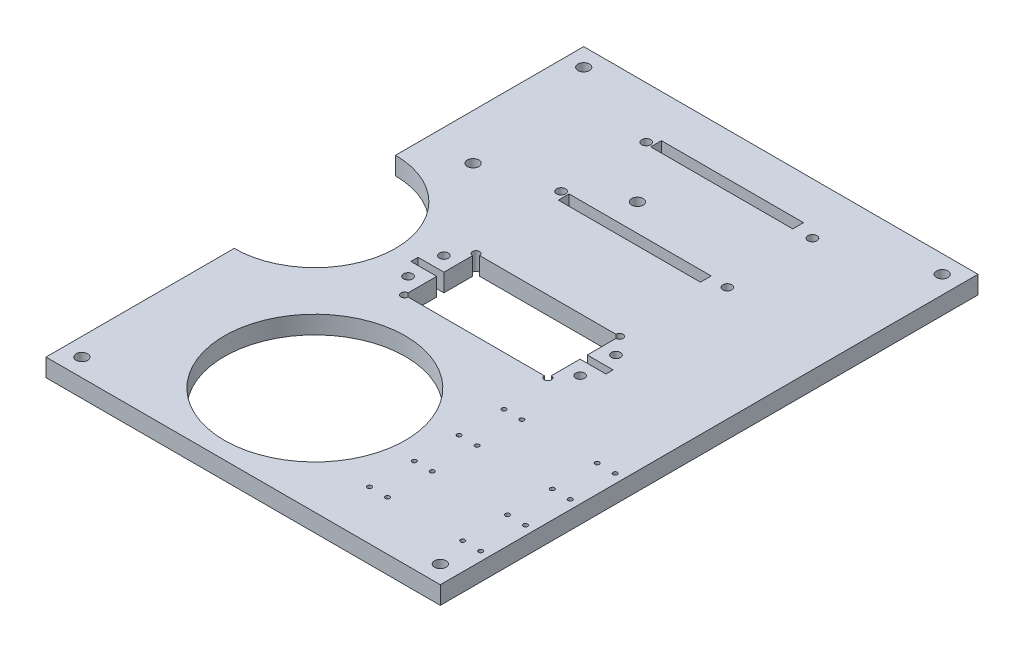
SolidWorks part; units mm, degrees
ref_plane "前基準面" through (0, 0, 0) normal (0, 0, 1) x (1, 0, 0)
ref_plane "上基準面" through (0, 0, 0) normal (0, 1, 0) x (1, 0, 0)
ref_plane "右基準面" through (0, 0, 0) normal (1, 0, 0) x (0, 0, -1)
sketch "草圖1" plane through (0, 0, 0) normal (0, 1, 0) x (1, 0, 0)
  line L0 (75, -9) -> (75, -1)
  line L1 (36, -10) -> (74, -10)
  line L2 (35, 9) -> (35, 1)
  line L3 (74, 10) -> (36, 10)
  line L4 (110, 75) -> (0, 75)
  line L5 (0, 75) -> (0, 22.5)
  line L6 (0, -22.5) -> (0, -75)
  line L7 (0, -75) -> (46, -75)
  line L8 (110, -75) -> (110, 75)
  line L9 (105, 70) -> (105, -70) construction
  line L10 (31.81, 60.625) -> (78.19, 60.625) construction
  line L11 (31.81, 60.625) -> (31.81, 36.875) construction
  line L12 (31.81, 36.875) -> (78.19, 36.875) construction
  line L13 (78.19, 60.625) -> (78.19, 36.875) construction
  line L15 (31, 5) -> (31, -5) construction
  line L16 (31, -5) -> (79, -5) construction
  line L17 (35, -1) -> (35, -9)
  line L18 (27.8, 1) -> (35, 1)
  line L19 (27.8, 1) -> (27.8, -1)
  line L20 (27.8, -1) -> (35, -1)
  line L21 (82.2, 1) -> (82.2, -1)
  line L22 (75, 1) -> (82.2, 1)
  line L23 (75, -1) -> (82.2, -1)
  line L24 (75, 1) -> (75, 9)
  line L25 (46, -75) -> (110, -75)
  line L36 (33.56, 63.125) -> (73.19, 63.125)
  line L37 (33.56, 63.125) -> (33.56, 60.125)
  line L38 (33.56, 60.125) -> (73.19, 60.125)
  line L39 (73.19, 63.125) -> (73.19, 60.125)
  line L40 (33.56, 37.375) -> (73.19, 37.375)
  line L41 (33.56, 37.375) -> (33.56, 34.375)
  line L42 (33.56, 34.375) -> (73.19, 34.375)
  line L43 (73.19, 37.375) -> (73.19, 34.375)
  circle A1 centre (76.5, -61.25) radius 0.6
  circle A3 centre (5, 70) radius 1.6
  circle A4 centre (5, -70) radius 1.6
  circle A5 centre (105, -70) radius 1.6
  circle A6 centre (105, 70) radius 1.6
  arc A8 (75, 9) -> (74, 10) centre (75, 10) ccw
  arc A9 (74, -10) -> (75, -9) centre (75, -10) ccw
  arc A10 (35, -9) -> (36, -10) centre (35, -10) ccw
  arc A11 (36, 10) -> (35, 9) centre (35, 10) ccw
  arc A34 (46, -70.2302) -> (46, -19.7698) centre (45, -45) ccw
  circle A37 centre (79, 5) radius 1.2295 construction
  circle A38 centre (31, -5) radius 1.2295 construction
  circle A39 centre (31, 5) radius 1.2295 construction
  circle A40 centre (79, -5) radius 1.2295 construction
  circle A41 centre (107.5, -61.25) radius 0.6
  circle A42 centre (107.5, -48.75) radius 0.6
  circle A43 centre (102.5, -48.75) radius 0.6
  circle A44 centre (107.5, -23.75) radius 0.6
  circle A45 centre (102.5, -36.25) radius 0.6
  circle A46 centre (81.5, -48.75) radius 0.6
  circle A56 centre (102.5, -23.75) radius 0.6
  circle A57 centre (107.5, -36.25) radius 0.6
  circle A58 centre (102.5, -61.25) radius 0.6
  circle A59 centre (81.5, -36.25) radius 0.6
  circle A60 centre (76.5, -48.75) radius 0.6
  circle A61 centre (81.5, -61.25) radius 0.6
  circle A62 centre (81.5, -23.75) radius 0.6
  circle A63 centre (76.5, -36.25) radius 0.6
  circle A70 centre (76.5, -23.75) radius 0.6
  arc A81 (0, -22.5) -> (0, 22.5) centre (0, 0) ccw
  arc A82 (46, -19.7698) -> (46, -70.2302) centre (45, -45) ccw
  circle A85 centre (78.19, 60.6222) radius 1.5 construction
  arc A90 (-289.1859, 122.3111) -> (-289.1859, 166.1859) centre (-294.1859, 144.2485) ccw
  circle A91 centre (45, 45) radius 1.6
  circle A92 centre (12.755, 31.3889) radius 1.6
  point P24 (0, 0)
  point P30 (55, -5)
  point P31 (55, -10)
  point P39 (27.8, 0)
  point P40 (82.2, 0)
  point P43 (55, 60.625)
  point P44 (55, 75)
  point P45 (31.81, 48.75)
  point P46 (0, 48.75)
  point P47 (31, 0)
  dimension "D1" = 50.5
  dimension "D4" = 110
  dimension "D8" = 3.2
  dimension "D9" = 22.5
  dimension "D18" = 1
  dimension "D20" = 2.459
  dimension "D21" = 1.2
  dimension "D31" = 7.2
  dimension "D2" = 46.38
  dimension "D3" = 23.75
  dimension "D5" = 150
  dimension "D6" = 140
  dimension "D10" = 30
  dimension "D11" = 45
  dimension "D12" = 100
  dimension "D13" = 5
  dimension "D14" = 10
  dimension "D15" = 48
  dimension "D16" = 40
  dimension "D17" = 20
  dimension "D19" = 35
  dimension "D22" = 5
  dimension "D23" = 5
  dimension "D24" = 21
  dimension "D25" = 12.5
  dimension "D26" = 12.5
  dimension "D27" = 12.5
  dimension "D28" = 76.5
  dimension "D29" = 13.75
  dimension "D30" = 2
  dimension "D33" = 3
  dimension "D34" = 0.5
  dimension "D35" = 0.5
  dimension "D36" = 1.75
  dimension "D37" = 5
extrude "填料-伸長1" add sketch "草圖1" against normal blind 5 contours A81 L6 L7 L8 L4 L5 A70 A63 A62 A61 A60 A59 A58 A57 A56 A46 A45 A44 A43 A42 A41 A34 A11 L3 A8 L0 A9 L1 A10 L2 A6 A5
hole_wizard "M3 螺紋孔1" positions "草圖6" profile "草圖7" tap size "M3" standard "ISO" end condition through all
sketch "草圖6" plane through (0, 0, 0) normal (0, 1, 0) x (1, 0, 0)
  point P0 (31, 5)
  point P3 (31, -5)
  point P6 (79, -5)
  point P9 (79, 5)
  point P12 (31.81, 36.875)
  point P15 (31.81, 60.625)
  point P18 (78.19, 60.625)
  point P21 (78.19, 36.875)
sketch "草圖7" plane through (31, 0, -5) normal (1, 0, 0) x (0, 0, 1)
  line L0 (0, 0) -> (0, 5)
  line L1 (0, 5) -> (1.25, 5)
  line L2 (1.25, 5) -> (1.25, 0)
  line L5 (1.25, 0) -> (0, 0)
  line L11 (0, -6.35) -> (0, 107.95) construction
  dimension "貫穿螺孔鑽直徑" = 2.5
  dimension "貫穿螺孔鑽深度" = 5
cosmetic thread "鑽孔螺紋1" parameters "D2"=3
cosmetic thread "鑽孔螺紋2" parameters "D2"=3
cosmetic thread "鑽孔螺紋3" parameters "D2"=3
cosmetic thread "鑽孔螺紋4" parameters "D2"=3
cosmetic thread "鑽孔螺紋5" parameters "D2"=3
cosmetic thread "鑽孔螺紋6" parameters "D2"=3
cosmetic thread "鑽孔螺紋7" parameters "D2"=3
cosmetic thread "鑽孔螺紋8" parameters "D2"=3
